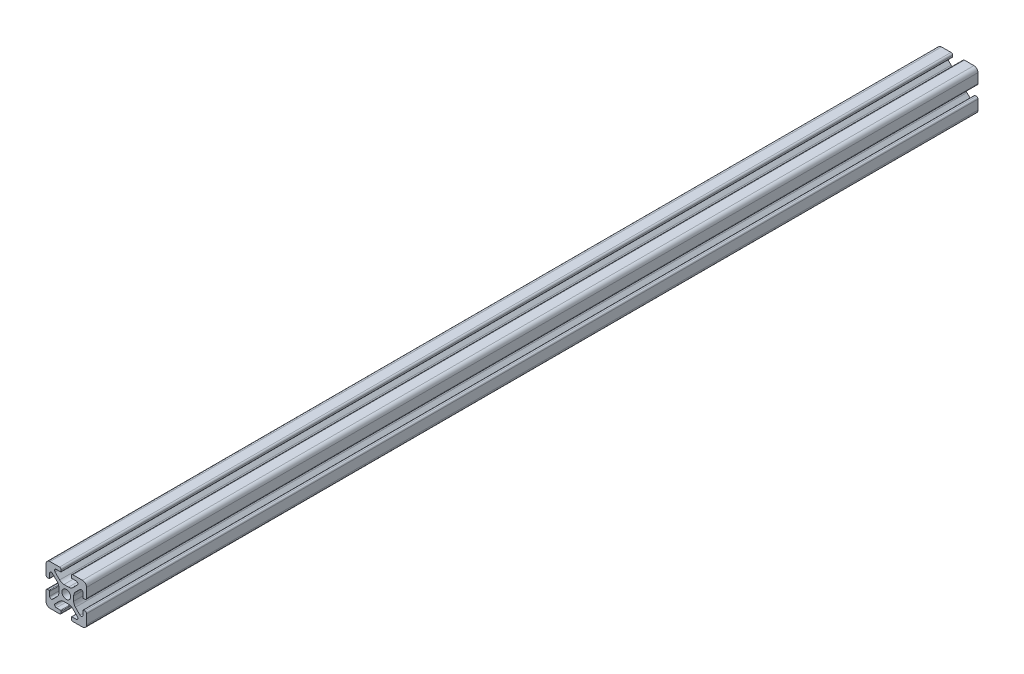
SolidWorks part; units mm, degrees
material "Alliage 1060"
ref_plane "Plan de face" through (0, 0, 0) normal (0, 0, 1) x (1, 0, 0)
ref_plane "Plan de dessus" through (0, 0, 0) normal (0, 1, 0) x (1, 0, 0)
ref_plane "Plan de droite" through (0, 0, 0) normal (1, 0, 0) x (0, 0, -1)
sketch "Esquisse1" plane through (0, 0, 0) normal (0, 0, 1) x (1, 0, 0)
  line L108 (-3.2559, 4.5287) -> (-5.5062, 6.779)
  line L109 (-4.9176, 8.2) -> (-2.8, 8.2)
  line L110 (-2.5, 8.5) -> (-2.5, 9.2)
  line L111 (-3.3, 10) -> (-8, 10)
  line L112 (-10, 8) -> (-10, 3.3)
  line L113 (-9.2, 2.5) -> (-8.5, 2.5)
  line L114 (-8.2, 2.8) -> (-8.2, 4.9176)
  line L115 (-6.779, 5.5062) -> (-4.5287, 3.2559)
  line L116 (-3.65, 1.1346) -> (-3.65, -1.1346)
  line L117 (-4.5287, -3.2559) -> (-6.779, -5.5062)
  line L118 (-8.2, -4.9176) -> (-8.2, -2.8)
  line L119 (-8.5, -2.5) -> (-9.2, -2.5)
  line L120 (-10, -3.3) -> (-10, -8)
  line L121 (-8, -10) -> (-3.3, -10)
  line L122 (-2.5, -9.2) -> (-2.5, -8.5)
  line L123 (-2.8, -8.2) -> (-4.9176, -8.2)
  line L124 (-5.5062, -6.779) -> (-3.2559, -4.5287)
  line L125 (-1.1346, -3.65) -> (1.1346, -3.65)
  line L126 (3.2559, -4.5287) -> (5.5062, -6.779)
  line L127 (4.9176, -8.2) -> (2.8, -8.2)
  line L128 (2.5, -8.5) -> (2.5, -9.2)
  line L129 (3.3, -10) -> (8, -10)
  line L130 (10, -8) -> (10, -3.3)
  line L131 (9.2, -2.5) -> (8.5, -2.5)
  line L132 (8.2, -2.8) -> (8.2, -4.9176)
  line L133 (6.779, -5.5062) -> (4.5287, -3.2559)
  line L134 (3.65, -1.1346) -> (3.65, 1.1346)
  line L135 (4.5287, 3.2559) -> (6.779, 5.5062)
  line L136 (8.2, 4.9176) -> (8.2, 2.8)
  line L137 (8.5, 2.5) -> (9.2, 2.5)
  line L138 (10, 3.3) -> (10, 8)
  line L139 (8, 10) -> (3.3, 10)
  line L140 (2.5, 9.2) -> (2.5, 8.5)
  line L141 (2.8, 8.2) -> (4.9176, 8.2)
  line L142 (5.5062, 6.779) -> (3.2559, 4.5287)
  line L143 (1.1346, 3.65) -> (-1.1346, 3.65)
  arc A42 (-2.15, 0) -> (2.15, 0) centre (0, 0) ccw
  arc A43 (2.15, 0) -> (-2.15, 0) centre (0, 0) ccw
  arc A108 (-4.9176, 8.2) -> (-5.5062, 6.779) centre (-4.9176, 7.3676) ccw
  arc A109 (-2.8, 8.2) -> (-2.5, 8.5) centre (-2.8, 8.5) ccw
  arc A110 (-2.5, 9.2) -> (-3.3, 10) centre (-3.3, 9.2) ccw
  arc A111 (-8, 10) -> (-10, 8) centre (-8, 8) ccw
  arc A112 (-10, 3.3) -> (-9.2, 2.5) centre (-9.2, 3.3) ccw
  arc A113 (-8.5, 2.5) -> (-8.2, 2.8) centre (-8.5, 2.8) ccw
  arc A114 (-6.779, 5.5062) -> (-8.2, 4.9176) centre (-7.3676, 4.9176) ccw
  arc A115 (-3.65, 1.1346) -> (-4.5287, 3.2559) centre (-6.65, 1.1346) ccw
  arc A116 (-4.5287, -3.2559) -> (-3.65, -1.1346) centre (-6.65, -1.1346) ccw
  arc A117 (-8.2, -4.9176) -> (-6.779, -5.5062) centre (-7.3676, -4.9176) ccw
  arc A118 (-8.2, -2.8) -> (-8.5, -2.5) centre (-8.5, -2.8) ccw
  arc A119 (-9.2, -2.5) -> (-10, -3.3) centre (-9.2, -3.3) ccw
  arc A120 (-10, -8) -> (-8, -10) centre (-8, -8) ccw
  arc A121 (-3.3, -10) -> (-2.5, -9.2) centre (-3.3, -9.2) ccw
  arc A122 (-2.5, -8.5) -> (-2.8, -8.2) centre (-2.8, -8.5) ccw
  arc A123 (-5.5062, -6.779) -> (-4.9176, -8.2) centre (-4.9176, -7.3676) ccw
  arc A124 (-1.1346, -3.65) -> (-3.2559, -4.5287) centre (-1.1346, -6.65) ccw
  arc A125 (3.2559, -4.5287) -> (1.1346, -3.65) centre (1.1346, -6.65) ccw
  arc A126 (4.9176, -8.2) -> (5.5062, -6.779) centre (4.9176, -7.3676) ccw
  arc A127 (2.8, -8.2) -> (2.5, -8.5) centre (2.8, -8.5) ccw
  arc A128 (2.5, -9.2) -> (3.3, -10) centre (3.3, -9.2) ccw
  arc A129 (8, -10) -> (10, -8) centre (8, -8) ccw
  arc A130 (10, -3.3) -> (9.2, -2.5) centre (9.2, -3.3) ccw
  arc A131 (8.5, -2.5) -> (8.2, -2.8) centre (8.5, -2.8) ccw
  arc A132 (6.779, -5.5062) -> (8.2, -4.9176) centre (7.3676, -4.9176) ccw
  arc A133 (3.65, -1.1346) -> (4.5287, -3.2559) centre (6.65, -1.1346) ccw
  arc A134 (4.5287, 3.2559) -> (3.65, 1.1346) centre (6.65, 1.1346) ccw
  arc A135 (8.2, 4.9176) -> (6.779, 5.5062) centre (7.3676, 4.9176) ccw
  arc A136 (8.2, 2.8) -> (8.5, 2.5) centre (8.5, 2.8) ccw
  arc A137 (9.2, 2.5) -> (10, 3.3) centre (9.2, 3.3) ccw
  arc A138 (10, 8) -> (8, 10) centre (8, 8) ccw
  arc A139 (3.3, 10) -> (2.5, 9.2) centre (3.3, 9.2) ccw
  arc A140 (2.5, 8.5) -> (2.8, 8.2) centre (2.8, 8.5) ccw
  arc A141 (5.5062, 6.779) -> (4.9176, 8.2) centre (4.9176, 7.3676) ccw
  arc A142 (1.1346, 3.65) -> (3.2559, 4.5287) centre (1.1346, 6.65) ccw
  arc A143 (-3.2559, 4.5287) -> (-1.1346, 3.65) centre (-1.1346, 6.65) ccw
extrude "Boss.-Extru.1" add sketch "Esquisse1" along normal blind 440
